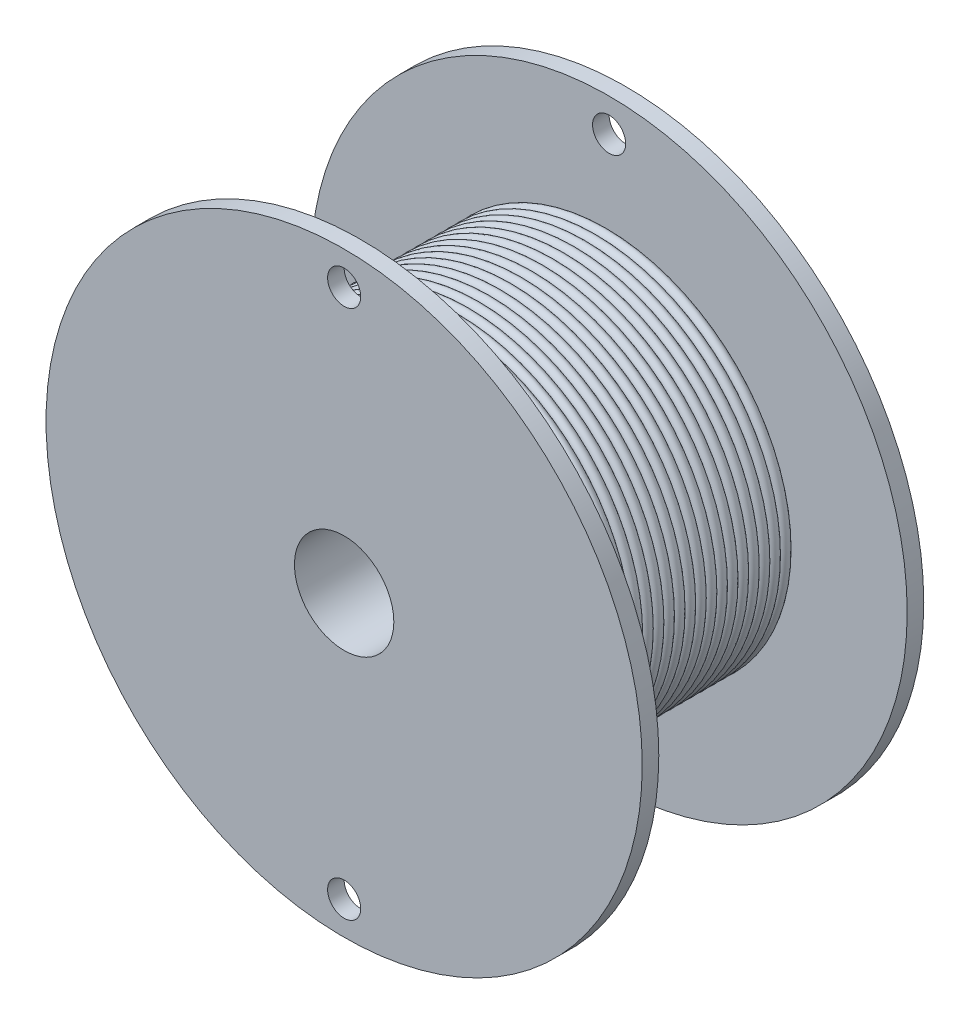
SolidWorks part; units mm, degrees
ref_plane "前基準面" through (0, 0, 0) normal (0, 0, 1) x (1, 0, 0)
ref_plane "上基準面" through (0, 0, 0) normal (0, 1, 0) x (1, 0, 0)
ref_plane "右基準面" through (0, 0, 0) normal (1, 0, 0) x (0, 0, -1)
sketch "草圖1" plane through (0, 0, 0) normal (0, 0, 1) x (1, 0, 0)
  circle A0 centre (0, 0) radius 90
  dimension "D1" = 180
extrude "填料-伸長1" add sketch "草圖1" along normal blind 5
sketch "草圖2" plane through (0, 0, 0) normal (0, 0, -1) x (-1, 0, 0)
  circle A0 centre (0, 0) radius 30
  dimension "D1" = 60
extrude "填料-伸長2" add sketch "草圖2" along normal blind 80
pattern_linear "直線複製排列1" count 2 spacing 80 along (0, 0, -1) of "填料-伸長1"
sketch "草圖5" plane through (0, 0, 0) normal (1, 0, 0) x (0, 0, -1)
  circle A0 centre (2.5303, 54.8418) radius 1.5322
  circle A1 centre (5.7303, 54.8418) radius 1.5322
  circle A2 centre (8.9303, 54.8418) radius 1.5322
  circle A3 centre (12.1303, 54.8418) radius 1.5322
  circle A4 centre (15.3303, 54.8418) radius 1.5322
  circle A5 centre (18.5303, 54.8418) radius 1.5322
  circle A6 centre (21.7303, 54.8418) radius 1.5322
  circle A7 centre (24.9303, 54.8418) radius 1.5322
  circle A8 centre (28.1303, 54.8418) radius 1.5322
  circle A9 centre (31.3303, 54.8418) radius 1.5322
  circle A10 centre (34.5303, 54.8418) radius 1.5322
  circle A11 centre (37.7303, 54.8418) radius 1.5322
  circle A12 centre (40.9303, 54.8418) radius 1.5322
  circle A13 centre (44.1303, 54.8418) radius 1.5322
  circle A14 centre (47.3303, 54.8418) radius 1.5322
  circle A15 centre (50.5303, 54.8418) radius 1.5322
  circle A16 centre (53.7303, 54.8418) radius 1.5322
  circle A17 centre (56.9303, 54.8418) radius 1.5322
  circle A18 centre (60.1303, 54.8418) radius 1.5322
  circle A19 centre (63.3303, 54.8418) radius 1.5322
  circle A20 centre (66.5303, 54.8418) radius 1.5322
  circle A21 centre (69.7303, 54.8418) radius 1.5322
  circle A22 centre (72.9303, 54.8418) radius 1.5322
  dimension "D1" = 23
revolve "旋轉2" add sketch "草圖5" angle 360 about axis through (0, 0, -80) along (0, 0, 1)
sketch "草圖6" plane through (0, 0, 5) normal (0, 0, 1) x (1, 0, 0)
  line L0 (0, 80) -> (0, -80) construction
  circle A0 centre (0, 0) radius 15
  circle A1 centre (0, 80) radius 5
  circle A2 centre (0, -80) radius 5
  circle A3 centre (0, 0) radius 90 construction
  dimension "D1" = 30
  dimension "D3" = 80
  dimension "D4" = 10
  dimension "D5" = 10
  dimension "D2" = 160
extrude "除料-伸長1" cut sketch "草圖6" against normal through all
